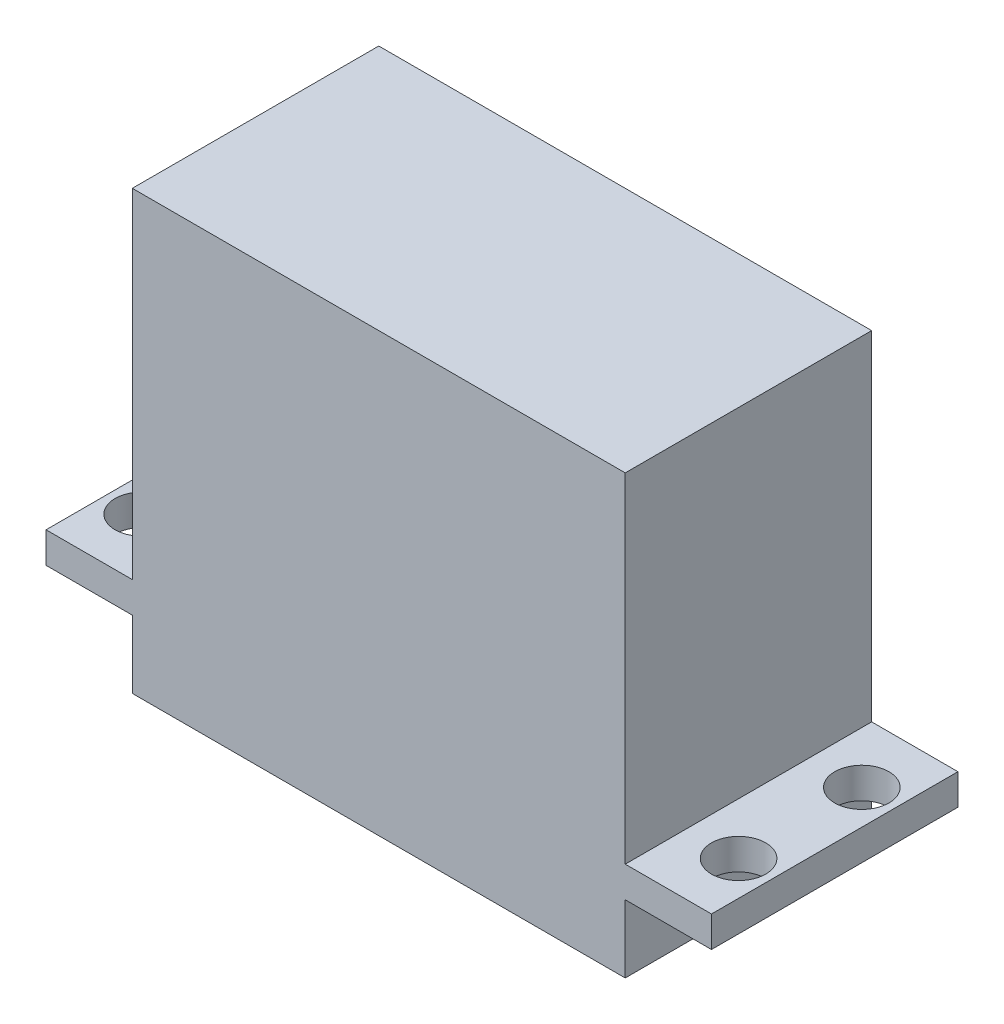
SolidWorks part; units mm, degrees
ref_plane "前视基准面" through (0, 0, 0) normal (0, 0, 1) x (1, 0, 0)
ref_plane "上视基准面" through (0, 0, 0) normal (0, 1, 0) x (1, 0, 0)
ref_plane "右视基准面" through (0, 0, 0) normal (1, 0, 0) x (0, 0, -1)
sketch "草图1" plane through (0, 0, 0) normal (0, 1, 0) x (1, 0, 0)
  line L1 (20, -10) -> (-20, -10)
  line L2 (20, -10) -> (20, 10)
  line L3 (20, 10) -> (-20, 10)
  line L4 (-20, -10) -> (-20, 10)
  line L5 (0, 10) -> (0, -10) construction
  line L6 (20, 0) -> (-20, 0) construction
  point P0 (0, 0)
extrude "凸台-拉伸2" add sketch "草图1" along normal blind 30
sketch "草图3" plane through (0, 0, 0) normal (0, 1, 0) x (1, 0, 0)
  line L1 (27, -10) -> (-27, -10)
  line L2 (27, -10) -> (27, 10)
  line L3 (27, 10) -> (-27, 10)
  line L4 (-27, -10) -> (-27, 10)
  line L5 (0, 10) -> (0, -10) construction
  line L6 (27, 0) -> (-27, 0) construction
  point P0 (0, 0)
extrude "凸台-拉伸3" add sketch "草图3" along normal blind 2.5
sketch "草图4" plane through (0, 0, 0) normal (0, 1, 0) x (1, 0, 0)
  line L0 (0, 0) -> (-24.2, 0)
  line L1 (0, 0) -> (24.2, 0)
  circle A0 centre (-24.2, -5) radius 2.2
  circle A1 centre (-24.2, 5) radius 2.2
  circle A2 centre (24.2, -5) radius 2.2
  circle A3 centre (24.2, 5) radius 2.2
extrude "切除-拉伸3" cut sketch "草图4" against normal through all and the other way through all contours A0 | A1 | A2 | A3
sketch "草图5" plane through (0, 0, 0) normal (0, 1, 0) x (1, 0, 0)
  line L0 (-27, -10) -> (27, -10) construction
  line L1 (20, 10) -> (-20, 10)
  line L2 (20, 10) -> (20, -10)
  line L3 (20, -10) -> (-20, -10)
  line L4 (-20, 10) -> (-20, -10)
  line L5 (0, -10) -> (0, 10) construction
  line L6 (20, 0) -> (-20, 0) construction
  point P0 (0, 0)
extrude "凸台-拉伸4" add sketch "草图5" against normal blind 5.5 from surface at 0 starting at face at (-24.2, 0, -2.8)
sketch "草图6" plane through (0, 0, 0) normal (0, 1, 0) x (1, 0, 0)
  circle A0 centre (-10, 0) radius 3
extrude "凸台-拉伸5" add sketch "草图6" against normal blind 7 from surface at -5.5 starting at face at (0, -5.5, 0)
